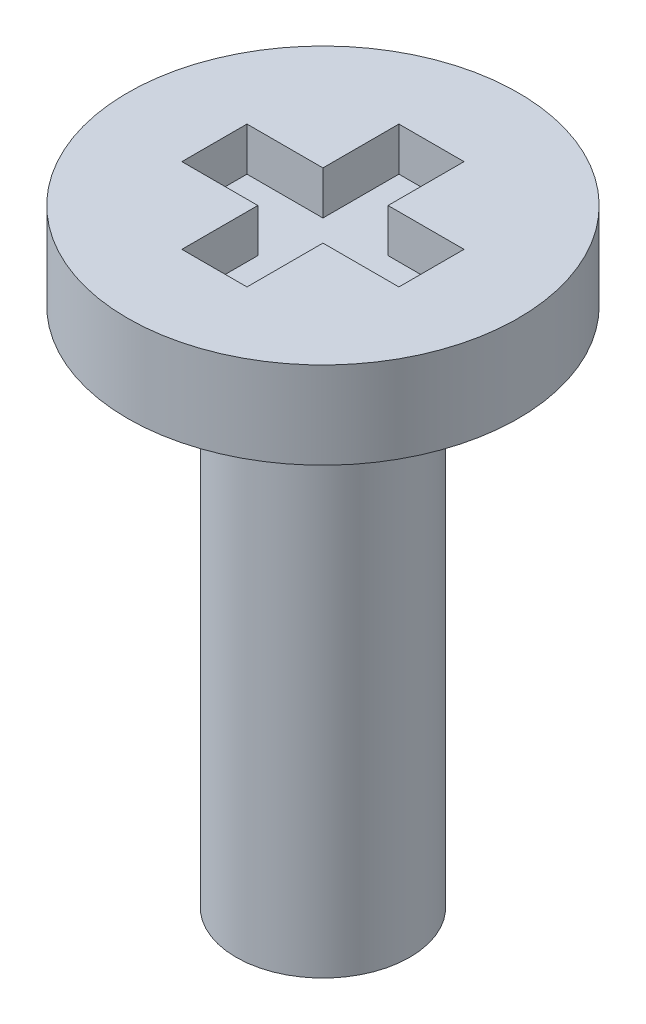
SolidWorks part; units mm, degrees
ref_plane "前视基准面" through (0, 0, 0) normal (0, 0, 1) x (1, 0, 0)
ref_plane "上视基准面" through (0, 0, 0) normal (0, 1, 0) x (1, 0, 0)
ref_plane "右视基准面" through (0, 0, 0) normal (1, 0, 0) x (0, 0, -1)
sketch "草图1" plane through (0, 0, 0) normal (0, 1, 0) x (1, 0, 0)
  circle A0 centre (0, 0) radius 1
  dimension "D1" = 2
extrude "拉伸1" add sketch "草图1" along normal blind 6
sketch "草图2" plane through (0, 6, 0) normal (0, 1, 0) x (-1, 0, 0)
  circle A0 centre (0, 0) radius 2.25
  dimension "D1" = 4.5
extrude "拉伸2" add sketch "草图2" along normal blind 1
sketch "草图3" plane through (0, 7, 0) normal (0, 1, 0) x (-1, 0, 0)
  line L0 (4.0624, 0) -> (-4.2778, 0) construction
  line L1 (0, -3.5166) -> (0, 3.738) construction
  line L3 (1.25, -0.375) -> (-1.25, -0.375)
  line L4 (1.25, -0.375) -> (1.25, 0.375)
  line L5 (1.25, 0.375) -> (-1.25, 0.375)
  line L6 (-1.25, -0.375) -> (-1.25, 0.375)
  dimension "D1" = 0.75
  dimension "D2" = 2.5
extrude "切除-拉伸1" cut sketch "草图3" against normal blind 0.5
sketch "草图4" plane through (0, 7, 0) normal (0, 1, 0) x (-1, 0, 0)
  line L0 (0, -3.8639) -> (0, 3.6765) construction
  line L1 (1.7727, 0) -> (-1.7019, 0) construction
  line L2 (0.375, -1.25) -> (-0.375, -1.25)
  line L3 (0.375, -1.25) -> (0.375, 1.25)
  line L4 (0.375, 1.25) -> (-0.375, 1.25)
  line L5 (-0.375, -1.25) -> (-0.375, 1.25)
  dimension "D1" = 0.75
  dimension "D2" = 2.5
extrude "切除-拉伸2" cut sketch "草图4" against normal blind 0.5
